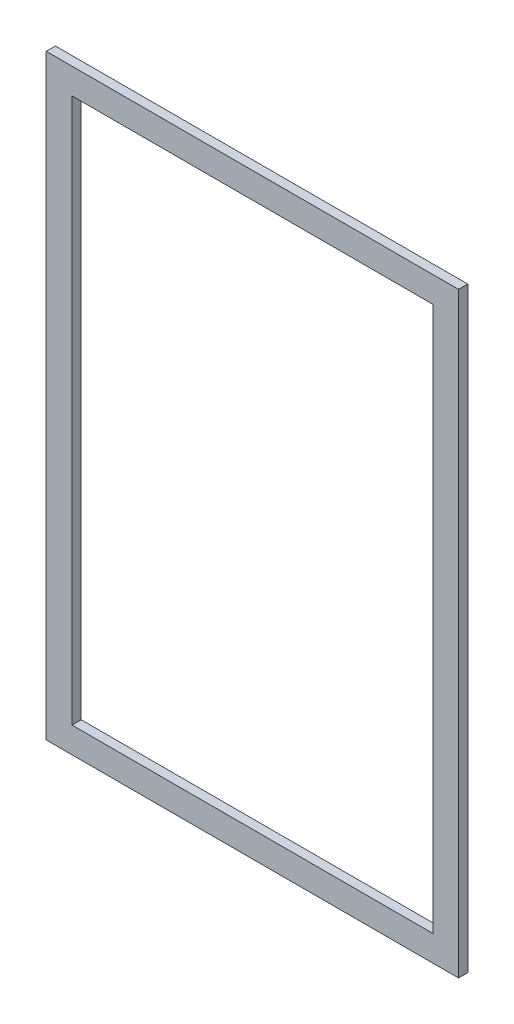
SolidWorks part; units mm, degrees
ref_plane "Front Plane" through (0, 0, 0) normal (0, 0, 1) x (1, 0, 0)
ref_plane "Top Plane" through (0, 0, 0) normal (0, 1, 0) x (1, 0, 0)
ref_plane "Right Plane" through (0, 0, 0) normal (1, 0, 0) x (0, 0, -1)
sketch "Sketch1" plane through (0, 0, 0) normal (0, 0, 1) x (1, 0, 0)
  line L1 (0, 0) -> (224, 0)
  line L2 (0, 0) -> (0, 324)
  line L3 (0, 324) -> (224, 324)
  line L4 (224, 0) -> (224, 324)
  line L5 (14, 14) -> (210, 14)
  line L6 (14, 14) -> (14, 310)
  line L7 (14, 310) -> (210, 310)
  line L8 (210, 14) -> (210, 310)
  dimension "D1" = 14
  dimension "D2" = 210
  dimension "D3" = 224
  dimension "D4" = 14
  dimension "D5" = 310
  dimension "D6" = 324
extrude "Profile" add sketch "Sketch1" along normal blind 5
equation "\"Profile_Depth\" = 5mm"
equation "\"D1@Profile\" = \"Profile_Depth\""
equation "\"Profile_Sketch_1\" = 14mm"
equation "\"D1@Sketch1\" = \"Profile_Sketch_1\""
equation "\"Profile_Sketch_2\" = 210mm"
equation "\"D2@Sketch1\" = \"Profile_Sketch_2\""
equation "\"Profile_Sketch_3\" = 224mm"
equation "\"D3@Sketch1\" = \"Profile_Sketch_3\""
equation "\"Profile_Sketch_4\" = 14mm"
equation "\"D4@Sketch1\" = \"Profile_Sketch_4\""
equation "\"Profile_Sketch_5\" = 310mm"
equation "\"D5@Sketch1\" = \"Profile_Sketch_5\""
equation "\"Profile_Sketch_6\" = 324mm"
equation "\"D6@Sketch1\" = \"Profile_Sketch_6\""
equation "\"EnvelopeWidth\" = 224mm"
equation "\"EnvelopeHeight\" = 324mm"
